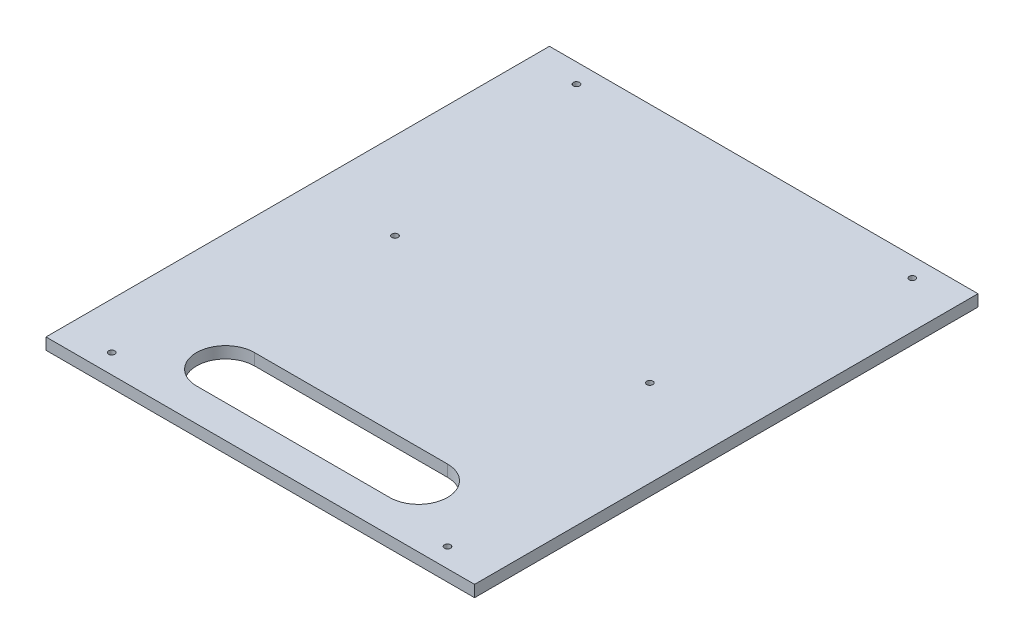
SolidWorks part; units mm, degrees
ref_plane "Front Plane" through (0, 0, 0) normal (0, 0, 1) x (1, 0, 0)
ref_plane "Top Plane" through (0, 0, 0) normal (0, 1, 0) x (1, 0, 0)
ref_plane "Right Plane" through (0, 0, 0) normal (1, 0, 0) x (0, 0, -1)
sketch "Sketch1" plane through (0, 0, 0) normal (0, 1, 0) x (1, 0, 0)
  line L0 (-111, 125.6127) -> (111, 125.6127)
  line L1 (-111, 125.6127) -> (-111, -125.6127)
  line L3 (111, 125.6127) -> (111, -125.6127)
  line L4 (-111, 125.6127) -> (111, -125.6127) construction
  line L5 (-111, -125.6127) -> (111, 125.6127) construction
  line L8 (-111, -125.6127) -> (-111, -165.6127)
  line L9 (-111, -165.6127) -> (111, -165.6127)
  line L10 (111, -125.6127) -> (111, -165.6127)
  point P10 (0, 0)
  dimension "D1" = 222
  dimension "D2" = 40
extrude "Boss-Extrude1" add sketch "Sketch1" along normal blind 6
sketch "Sketch2" plane through (0, 6, 0) normal (0, 1, 0) x (1, 0, 0)
  circle A0 centre (-57, 100.5142) radius 1.6
sketch "Sketch3" plane through (0, 0, 0) normal (0, -1, 0) x (1, 0, 0)
  line L0 (-111, -125.6127) -> (-111, 165.6127) construction
  line L1 (111, -125.6127) -> (-111, -125.6127)
  line L2 (111, -125.6127) -> (111, -95.1873)
  line L3 (111, -95.1873) -> (-111, -95.1873)
  line L4 (-111, -125.6127) -> (-111, -95.1873)
  circle A0 centre (66, 29.8127) radius 1.6
  circle A1 centre (-66, 29.8127) radius 1.6
  dimension "D1" = 3.2
extrude "Cut-Extrude1" cut sketch "Sketch3" against normal blind 10
sketch "Sketch4" plane through (0, 0, 0) normal (0, -1, 0) x (1, 0, 0)
  circle A0 centre (87, 155.6127) radius 1.6
  circle A1 centre (-87, 155.6127) radius 1.6
  circle A2 centre (87, -85.1873) radius 1.6
  circle A3 centre (-87, -85.1873) radius 1.6
extrude "Cut-Extrude2" cut sketch "Sketch4" against normal blind 10
sketch "Sketch5" plane through (0, 6, 0) normal (0, 1, 0) x (1, 0, 0)
  line L0 (-50, -118.6127) -> (50, -118.6127) construction
  line L1 (50, -148.6127) -> (-50, -148.6127) construction
  line L2 (-50, -118.6127) -> (50, -118.6127)
  line L3 (50, -148.6127) -> (-50, -148.6127)
  arc A0 (-50, -118.6127) -> (-50, -148.6127) centre (-50, -133.6127) ccw construction
  arc A1 (50, -148.6127) -> (50, -118.6127) centre (50, -133.6127) ccw construction
  arc A2 (-50, -118.6127) -> (-50, -148.6127) centre (-50, -133.6127) ccw
  arc A3 (50, -148.6127) -> (50, -118.6127) centre (50, -133.6127) ccw
extrude "Cut-Extrude3" cut sketch "Sketch5" against normal blind 10
